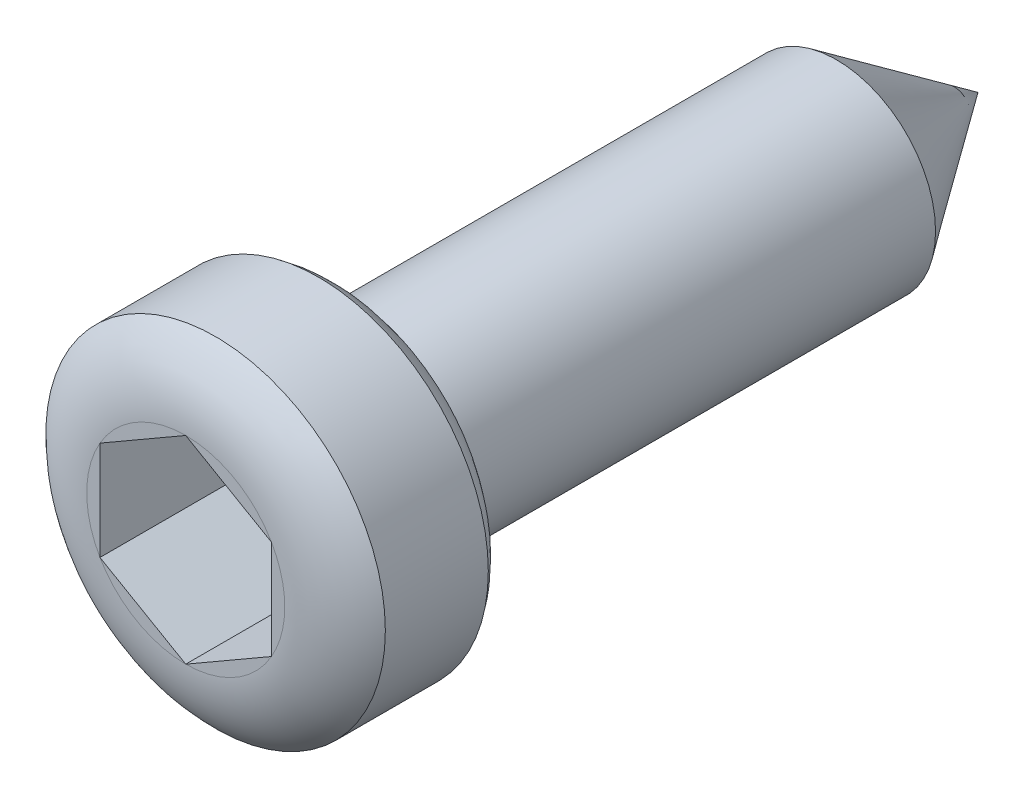
SolidWorks part; units mm, degrees
ref_plane "Front Plane" through (0, 0, 0) normal (0, 0, 1) x (1, 0, 0)
ref_plane "Top Plane" through (0, 0, 0) normal (0, 1, 0) x (1, 0, 0)
ref_plane "Right Plane" through (0, 0, 0) normal (1, 0, 0) x (0, 0, -1)
sketch "Sketch1" plane through (0, 0, 0) normal (1, 0, 0) x (0, 0, -1)
  line L0 (0, 0) -> (14, 0)
  line L1 (0.5274, 3) -> (2.3468, 3)
  line L4 (11.5, 1.75) -> (14, 0)
  line L5 (0, 0) -> (0, 1.75)
  line L7 (3.0177, 1.75) -> (11.5, 1.75)
  arc A2 (0, 1.75) -> (0.5274, 3) centre (1.7449, 1.75) cw
  arc A3 (3.0177, 1.75) -> (2.3468, 3) centre (1.5177, 1.75) ccw
  point P5 (0, 0)
  point P6 (0, 0)
  dimension "D6" = 1.7449
  dimension "D7" = 1.5
  dimension "D1" = 3
  dimension "D2" = 14
  dimension "D3" = 1.75
  dimension "D4" = 2.5
revolve "Revolve1" add sketch "Sketch1" angle 360 about L0
sketch "Sketch7" plane through (0, 0, 0) normal (0, 0, 1) x (1, 0, 0)
  line L1 (0, -1.75) -> (1.5155, -0.875)
  line L2 (1.5155, -0.875) -> (1.5155, 0.875)
  line L3 (1.5155, 0.875) -> (0, 1.75)
  line L4 (0, 1.75) -> (-1.5155, 0.875)
  line L5 (-1.5155, 0.875) -> (-1.5155, -0.875)
  line L6 (-1.5155, -0.875) -> (0, -1.75)
  circle A0 centre (0, 0) radius 1.5155 construction
  circle A1 centre (0, 0) radius 1.75
  circle A2 centre (0, 0) radius 1.75
  point P0 (0, 1.75)
  dimension "D1" = 0
extrude "Cut-Extrude1" cut sketch "Sketch7" against normal blind 2.5 contours L5 L6 L1 L2 L3 L4
